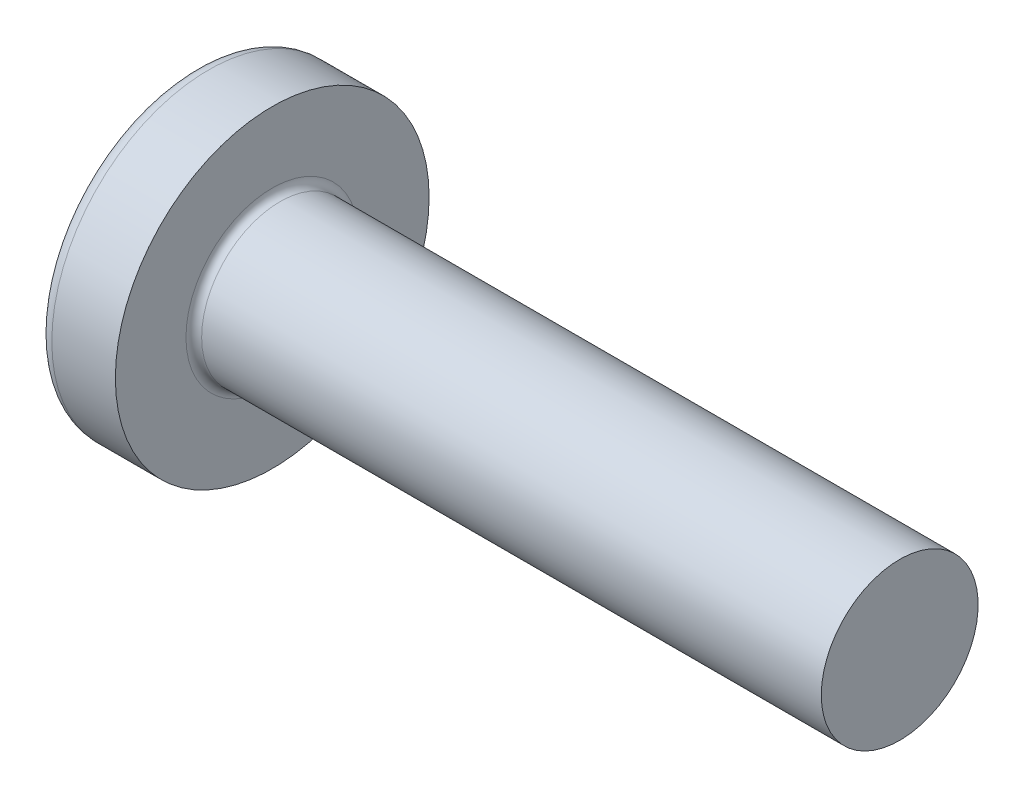
SolidWorks part; units mm, degrees
ref_plane "Plane1" through (0, 0, 0) normal (0, 0, 1) x (1, 0, 0)
ref_plane "Plane2" through (0, 0, 0) normal (0, 1, 0) x (1, 0, 0)
ref_plane "Plane3" through (0, 0, 0) normal (1, 0, 0) x (0, 0, -1)
sketch "BodySke" plane through (0, 0, 0) normal (0, 0, 1) x (1, 0, 0)
  line L0 (1.6, 1) -> (1.6, 2)
  line L1 (1.8, 6.35) -> (1.8, -3.175) construction
  line L2 (-25.4, 0) -> (127, 0) construction
  line L3 (9.6, 0) -> (0, 0)
  line L4 (1.6, 1) -> (9.6, 1)
  line L5 (9.6, 1) -> (9.6, 0)
  line L6 (0.79, 2) -> (1.6, 2)
  line L8 (1.6, 6.35) -> (1.6, -3.175) construction
  arc A0 (0.6464, 1.9285) -> (0, 0) centre (3.2, 0) ccw
  arc A2 (0.6464, 1.9285) -> (0.79, 2) centre (0.79, 1.82) cw
  dimension "Head_crown_rad" = 3.2
  dimension "Head_fillet_rad" = 0.18
  dimension "Length" = 8
  dimension "Head_ht" = 1.6
  dimension "Head_dia" = 4
  dimension "Advance" = 0.4
  dimension "Thread_nom" = 8
  dimension "Diameter" = 2
revolve "Base-Revolve" add sketch "BodySke"
cosmetic thread "ThreadCosmetic" [suppressed]
fillet "Fillet1" radius 0.1 1 edges at (1.6, 0, 1)
sketch "Sketch3" plane through (0, 0, 0) normal (1, 0, 0) x (0, 0, -1)
  line L0 (0.24, -1.05) -> (-0.24, -1.05)
  line L1 (0.24, -1.05) -> (0.24, 1.05)
  line L2 (-0.24, 1.05) -> (0.24, 1.05)
  line L3 (-0.24, 1.05) -> (-0.24, -1.05)
  dimension "Cross_dia" = 2.1
  dimension "D1" = 1.05
  dimension "Cross_width" = 0.48
  dimension "D2" = 0.24
ref_plane "Plane4" through (1.42, 0, 0) normal (1, 0, 0) x (0, 0, -1)
sketch "Sketch4" plane through (1.42, 0, 0) normal (1, 0, 0) x (0, 0, -1)
  line L0 (0.24, -0.342) -> (-0.24, -0.342)
  line L1 (0.24, -0.342) -> (0.24, 0.342)
  line L2 (-0.24, 0.342) -> (0.24, 0.342)
  line L3 (-0.24, 0.342) -> (-0.24, -0.342)
  dimension "D1" = 0.48
  dimension "D2" = 0.684
  dimension "D3" = 0.24
  dimension "D4" = 0.342
loft "Recess" cut profiles "Sketch3", "Sketch4"
pattern_circular "RecPat" count 2 every 90 about axis through (0, 0, 0) along (1, 0, 0) of "Recess"
sketch "RecCorSke" plane through (0, 0, 0) normal (0, 0, 1) x (1, 0, 0)
  line L0 (-3.175, 0) -> (15.875, 0) construction
  line L1 (-25.4, 0) -> (127, 0) construction
  line L2 (0, 0) -> (0, 0.4548)
  line L3 (0, 0.4548) -> (1.42, 0.3555)
  line L4 (1.42, 0.3555) -> (1.5355, 0)
  line L5 (1.5355, 0) -> (0, 0)
  dimension "Diameter" = 0.711
  dimension "Depth" = 1.42
  dimension "Draft_angle" = 4
  dimension "Bottom_angle" = 18
revolve "RecessCore" cut sketch "RecCorSke" angle 360 about L0
sketch "ThdSchSke" plane through (0, 0, 0) normal (0, 0, 1) x (1, 0, 0)
  line L0 (2.4, -0.774) -> (2.2418, -1)
  line L1 (2.4, -0.774) -> (2.5582, -1)
  line L2 (2.5582, -1) -> (2.5582, -1.25)
  line L3 (-3.175, 0) -> (5.1513, 0) construction
  line L5 (2.5582, -1.25) -> (2.2418, -1.25)
  line L6 (2.2418, -1.25) -> (2.2418, -1)
  dimension "Diameter" = 2
  dimension "SideAngle" = 55
  dimension "VeeAngle" = 70
  dimension "Thread_minor" = 1.548
  dimension "Overcut" = 2.5
  dimension "Start" = 2.4
revolve "ThreadSchematic" [suppressed] cut sketch "ThdSchSke" angle 360 about L3
pattern_linear "ThdSchPat" [suppressed]
equation "\"D1@Sketch3\" = \"Cross_dia@Sketch3\" / 2"
equation "\"D2@Sketch3\" = \"Cross_width@Sketch3\" / 2"
equation "\"Depth@RecCorSke\" = \"Cross_depth@Plane4\""
equation "\"D1@Sketch4\" = \"Cross_width@Sketch3\""
equation "\"D2@Sketch4\" = \"Cross_dia@Sketch3\" - 2.0 * \"Cross_depth@Plane4\" * tan(26.5  * 0.017453292)"
equation "\"D3@Sketch4\" = \"D1@Sketch4\" / 2"
equation "\"D4@Sketch4\" = \"D2@Sketch4\" / 2"
equation "\"Thread_length@ThreadCosmetic\" = ((sgn( (\"Length@BodySke\" - \"Advance@BodySke\" * 2.0 ) - \"Thread_nom@BodySke\" )-1)*( (\"Length@BodySke\" - \"Advance@BodySke\" * 2.0 ) - \"Thread_nom@BodySke\" ))/-2+ \"Thread_nom@BodySke\""
equation "\"Thread_minor@ThdSchSke\" = \"Thread_minor@ThreadCosmetic\""
equation "\"Diameter@ThdSchSke\" = \"Diameter@BodySke\""
equation "\"Overcut@ThdSchSke\" = \"Diameter@BodySke\" * 1.25"
equation "\"Start@ThdSchSke\" = \"Head_ht@BodySke\" + \"Length@BodySke\" - \"Thread_length@ThreadCosmetic\"  '---Non-countersunk---"
equation "\"Num_threads@ThdSchPat\" = int( \"Thread_length@ThreadCosmetic\" / \"Advance@BodySke\" + 0.999 )  + 1"
equation "\"Advance@ThdSchPat\" = \"Thread_length@ThreadCosmetic\" /  (\"Num_threads@ThdSchPat\" - 1) 'relax it"
